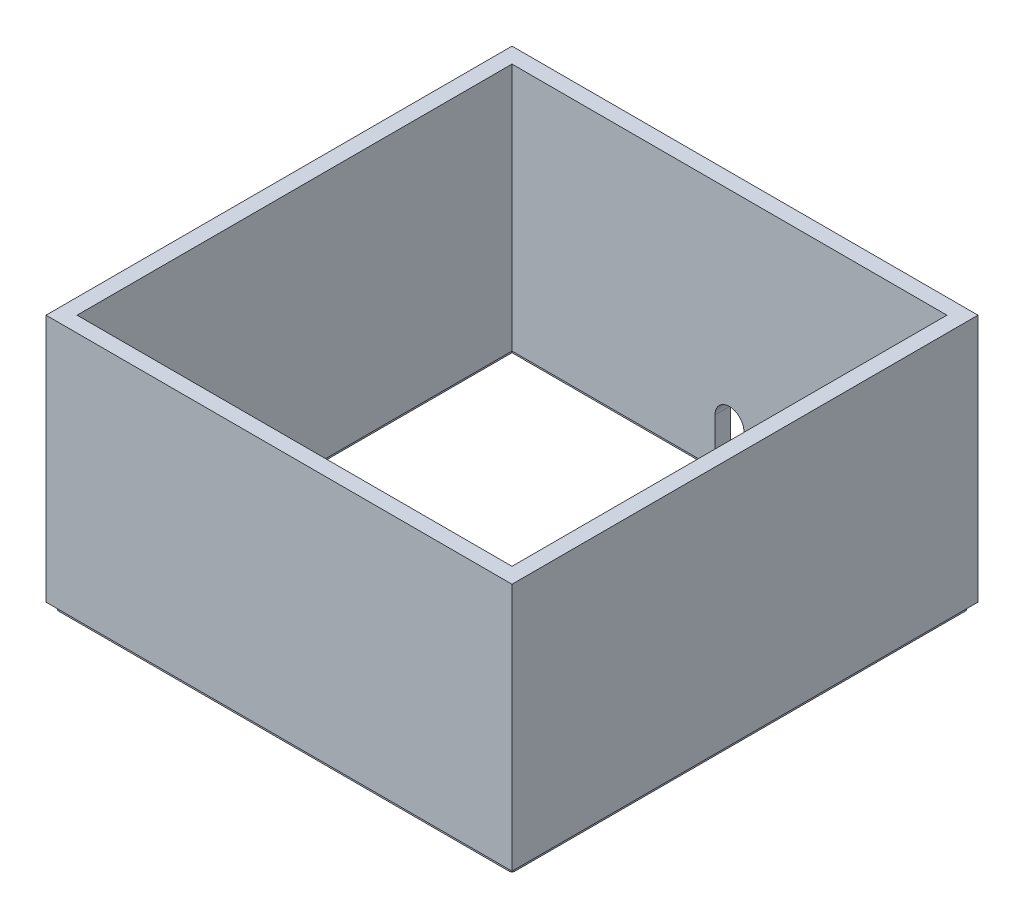
SolidWorks part; units mm, degrees
ref_plane "Front Plane" through (0, 0, 0) normal (0, 0, 1) x (1, 0, 0)
ref_plane "Top Plane" through (0, 0, 0) normal (0, 1, 0) x (1, 0, 0)
ref_plane "Right Plane" through (0, 0, 0) normal (1, 0, 0) x (0, 0, -1)
sketch "Sketch1" plane through (0, 91.9795, 0) normal (0, 1, 0) x (1, 0, 0)
  line L1 (137.6611, -186.5587) -> (-12.3389, -186.5587)
  line L2 (137.6611, -186.5587) -> (137.6611, -36.5587)
  line L3 (137.6611, -36.5587) -> (-12.3389, -36.5587)
  line L4 (-12.3389, -186.5587) -> (-12.3389, -36.5587)
  line L5 (132.6611, -181.5587) -> (-7.3389, -181.5587)
  line L6 (132.6611, -181.5587) -> (132.6611, -41.5587)
  line L7 (132.6611, -41.5587) -> (-7.3389, -41.5587)
  line L8 (-7.3389, -181.5587) -> (-7.3389, -41.5587)
extrude "Boss-Extrude1" add sketch "Sketch1" along normal blind 80
sketch "Sketch5" plane through (0, 91.9795, 0) normal (0, -1, 0) x (1, 0, 0)
  line L0 (-9.8389, 184.0587) -> (-9.8389, 39.0587) construction
  line L1 (-8.8639, 184.0587) -> (-8.8639, 39.0587)
  line L2 (-10.8139, 184.0587) -> (-10.8139, 39.0587)
  arc A0 (-8.8639, 184.0587) -> (-10.8139, 184.0587) centre (-9.8389, 184.0587) ccw
  arc A1 (-10.8139, 39.0587) -> (-8.8639, 39.0587) centre (-9.8389, 39.0587) ccw
  point P4 (-9.8389, 111.5587)
extrude "Boss-Extrude2" add sketch "Sketch5" along normal blind 2
pattern_circular "CirPattern1" count 4 every 90 about axis through (62.6611, 0, 111.5587) along (0, 1, 0) of "Boss-Extrude2"
sketch "Sketch6" plane through (0, 0, 36.5587) normal (0, 0, -1) x (-1, 0, 0)
  line L0 (-62.6611, 91.9795) -> (-62.6611, 106.8444) construction
  line L1 (-137.6611, 91.9795) -> (12.3389, 91.9795) construction
  line L2 (-67.3285, 91.9795) -> (-67.3285, 106.8444)
  line L3 (-57.9937, 91.9795) -> (-57.9937, 106.8444)
  line L6 (-67.3285, 91.9795) -> (-67.3285, 79.0203)
  line L7 (-67.3285, 79.0203) -> (-57.9937, 79.0203)
  line L8 (-57.9937, 91.9795) -> (-57.9937, 79.0203)
  arc A1 (-57.9937, 106.8444) -> (-67.3285, 106.8444) centre (-62.6611, 106.8444) ccw
  point P4 (-62.6611, 99.4119)
extrude "Cut-Extrude1" cut sketch "Sketch6" against normal blind 10
